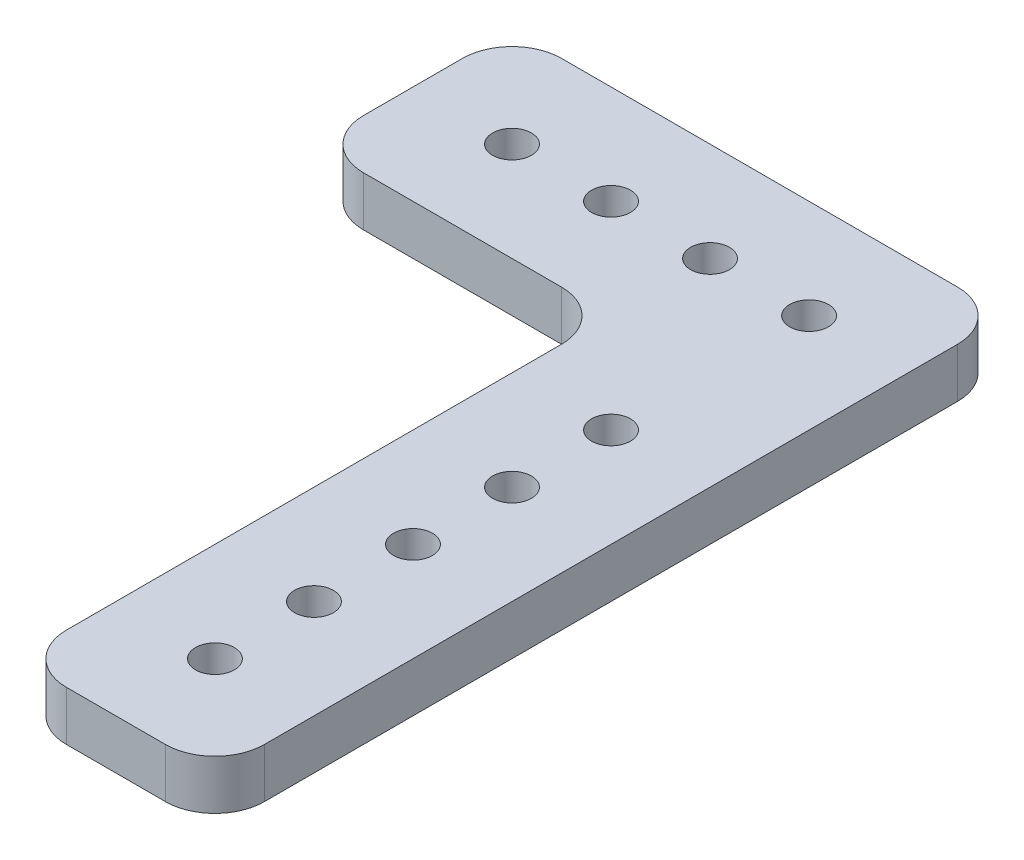
SolidWorks part; units mm, degrees
material "6061-T6 (SS)"
ref_plane "Front Plane" through (0, 0, 0) normal (0, 0, 1) x (1, 0, 0)
ref_plane "Top Plane" through (0, 0, 0) normal (0, 1, 0) x (1, 0, 0)
ref_plane "Right Plane" through (0, 0, 0) normal (1, 0, 0) x (0, 0, -1)
sketch "Sketch1" plane through (0, 0, 0) normal (0, 1, 0) x (1, 0, 0)
  line L0 (-38.1, 88.9) -> (25.4, 88.9) construction
  line L1 (0, 0) -> (25.4, 0)
  line L2 (0, 0) -> (0, 101.6)
  line L3 (0, 101.6) -> (25.4, 101.6)
  line L4 (25.4, 0) -> (25.4, 101.6)
  line L5 (25.4, 101.6) -> (-38.1, 101.6)
  line L6 (25.4, 101.6) -> (25.4, 76.2)
  line L7 (25.4, 76.2) -> (-38.1, 76.2)
  line L8 (-38.1, 101.6) -> (-38.1, 76.2)
  line L9 (12.7, 0) -> (12.7, 101.6) construction
  circle A0 centre (12.7, 88.9) radius 2.4892
  circle A1 centre (-25.4, 88.9) radius 2.4892
  circle A2 centre (-12.7, 88.9) radius 2.4892
  circle A3 centre (0, 88.9) radius 2.4892
  circle A4 centre (12.7, 63.5) radius 2.4892
  circle A5 centre (12.7, 50.8) radius 2.4892
  circle A6 centre (12.7, 38.1) radius 2.4892
  circle A7 centre (12.7, 25.4) radius 2.4892
  circle A8 centre (12.7, 12.7) radius 2.4892
  dimension "D6" = 4.9784
  dimension "D7" = 12.7
  dimension "D8" = 12.7
  dimension "D9" = 12.7
  dimension "D10" = 12.7
  dimension "D11" = 12.7
  dimension "D12" = 12.7
  dimension "D13" = 12.7
  dimension "D14" = 12.7
  dimension "D1" = 25.4
  dimension "D2" = 25.4
  dimension "D3" = 101.6
  dimension "D4" = 63.5
  dimension "D5" = 12.7
extrude "Boss-Extrude1" add sketch "Sketch1" along normal blind 6.35 contours A3 L2 L5 L8 L7 A2 A1 | A3 L2 L7 L4 L3 A0 | L4 L7 L2 L1 A8 A7 A6 A5 A4
fillet "Fillet1" radius 6.35 6 edges at (0, 3.175, 0) (0, 3.175, -76.2) (-38.1, 3.175, -76.2) (-38.1, 3.175, -101.6) (25.4, 3.175, -101.6) (25.4, 3.175, 0)
